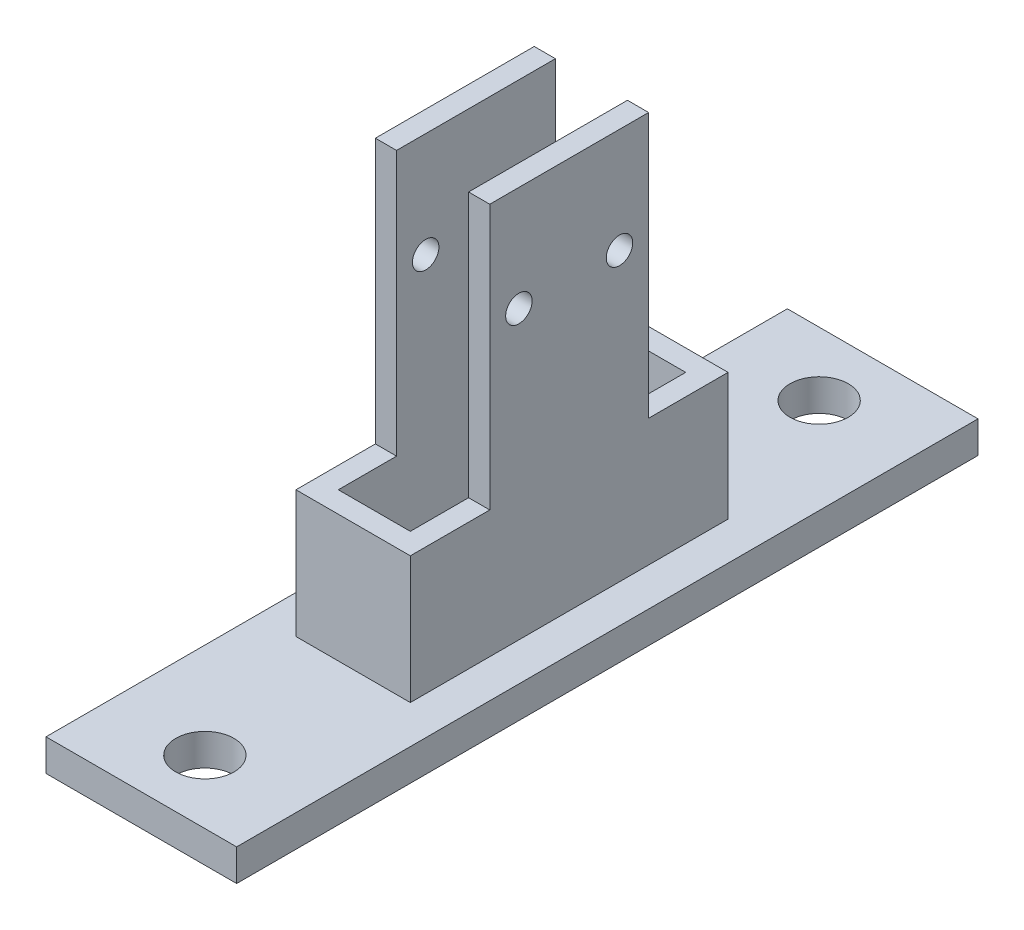
SolidWorks part; units mm, degrees
ref_plane "Front Plane" through (0, 0, 0) normal (0, 0, 1) x (1, 0, 0)
ref_plane "Top Plane" through (0, 0, 0) normal (0, 1, 0) x (1, 0, 0)
ref_plane "Right Plane" through (0, 0, 0) normal (1, 0, 0) x (0, 0, -1)
sketch "Sketch1" plane through (0, 0, 0) normal (0, 1, 0) x (1, 0, 0)
  line L1 (-22.5, 15) -> (22.5, 15)
  line L2 (-22.5, 15) -> (-22.5, -15)
  line L3 (-22.5, -15) -> (22.5, -15)
  line L4 (22.5, 15) -> (22.5, -15)
  line L5 (-22.5, 15) -> (22.5, -15) construction
  line L6 (-22.5, -15) -> (22.5, 15) construction
  point P0 (0, 0)
  dimension "D1" = 45
  dimension "D2" = 30
extrude "Boss-Extrude1" add sketch "Sketch1" along normal blind 3 contours L2 L1 L4 L3
ref_plane "Plane1" through (0, 0, -15) normal (0, 0, -1) x (-1, 0, 0)
ref_plane "Plane2" through (0, 0, 15) normal (0, 0, 1) x (1, 0, 0)
ref_plane "Plane3" through (3.4, 0, 0) normal (1, 0, 0) x (0, 0, -1)
ref_plane "Plane4" through (-3.4, 0, 0) normal (1, 0, 0) x (0, 0, -1)
sketch "Sketch3" plane through (-3.4, 0, 0) normal (1, 0, 0) x (0, 0, -1)
  line L0 (-15, 3) -> (-15, 0) construction
  line L1 (-7.5, 40) -> (7.5, 40)
  line L2 (-7.5, 40) -> (-7.5, 15)
  line L3 (-22.803, 0) -> (22.803, 0)
  line L4 (7.5, 40) -> (7.5, 15)
  line L7 (-7.5, 15) -> (-15, 15)
  line L8 (0, 0) -> (0, 40) construction
  line L9 (15, 0) -> (-15, 0) construction
  line L10 (15, 3) -> (15, 0) construction
  line L11 (15, 15) -> (7.5, 15)
  line L12 (15, 15) -> (15, 0)
  line L13 (15, 0) -> (-15, 0)
  line L14 (-15, 15) -> (-15, 0)
  line L15 (15, 15) -> (-15, 0) construction
  line L16 (15, 0) -> (-15, 15) construction
  circle A0 centre (-4.75, 30.1) radius 1.25
  circle A1 centre (4.75, 30.1) radius 1.25
  point P5 (0, 0)
  point P17 (0, 7.5)
  dimension "D3" = 2.5
  dimension "D1" = 40
  dimension "D2" = 15
  dimension "D4" = 9.5
  dimension "D5" = 4.75
  dimension "D6" = 30.1
  dimension "D7" = 15
extrude "Boss-Extrude2" add sketch "Sketch3" against normal blind 2 contours L7 L14 L13 L3 L12 L11 L4 L1 L2 A1 A0
mirror "Mirror1" about plane through (0, 0, 0) normal (1, 0, 0) of bodies 102
sketch "Sketch4" plane through (0, 0, 15) normal (0, 0, 1) x (1, 0, 0)
  line L1 (-5.4, 15) -> (5.4, 15)
  line L2 (-5.4, 15) -> (-5.4, 3)
  line L3 (-5.4, 3) -> (5.4, 3)
  line L4 (5.4, 15) -> (5.4, 3)
extrude "Boss-Extrude3" add sketch "Sketch4" against normal blind 2 contours L2 L1 L4 L3
mirror "Mirror2" about plane through (0, 0, 0) normal (0, 0, 1) of "Boss-Extrude3"
sketch "Sketch6" plane through (-5.4, 0, 0) normal (-1, 0, 0) x (0, 0, 1)
  line L0 (7.5, 40) -> (7.5, 15) construction
  line L1 (-7.5, 40) -> (7.5, 40)
  line L2 (-7.5, 40) -> (-7.5, 35.8403)
  line L3 (-7.5, 35.8403) -> (7.5, 35.8403)
  line L4 (7.5, 40) -> (7.5, 35.8403)
sketch "Sketch7" plane through (0, 3, 0) normal (0, 1, 0) x (1, 0, 0)
  line L0 (5.4, 15) -> (22.5, 15) construction
  line L1 (-12.5, 5) -> (12.5, 5)
  line L2 (-12.5, 5) -> (-12.5, -5)
  line L3 (-12.5, -5) -> (12.5, -5)
  line L4 (12.5, 5) -> (12.5, -5)
  line L5 (-12.5, 5) -> (12.5, -5) construction
  line L6 (-12.5, -5) -> (12.5, 5) construction
  line L7 (22.5, 15) -> (22.5, -15) construction
  point P0 (0, 0)
  dimension "D1" = 10
  dimension "D2" = 10
sketch "Sketch10" plane through (0, 3, 0) normal (0, 1, 0) x (1, 0, 0)
  line L1 (-9, 35) -> (9, 35)
  line L2 (-9, 35) -> (-9, -35)
  line L3 (-9, -35) -> (9, -35)
  line L4 (9, 35) -> (9, -35)
  line L5 (-9, 35) -> (9, -35) construction
  line L6 (-9, -35) -> (9, 35) construction
  point P0 (0, 0)
  dimension "D1" = 70
  dimension "D2" = 18
extrude "Boss-Extrude4" add sketch "Sketch10" against normal blind 3
sketch "Sketch11" plane through (0, 3, 0) normal (0, 1, 0) x (1, 0, 0)
  line L0 (-9, -15) -> (-9, -35) construction
  line L1 (-22.5, 15) -> (-9, 15)
  line L2 (-22.5, 15) -> (-22.5, -15)
  line L3 (-22.5, -15) -> (-9, -15)
  line L4 (-9, 15) -> (-9, -15)
  line L5 (-22.5, 15) -> (-9, -15) construction
  line L6 (-22.5, -15) -> (-9, 15) construction
  point P0 (-15.75, 0)
extrude "Cut-Extrude1" cut sketch "Sketch11" against normal blind 3
mirror "Mirror3" about plane through (0, 0, 0) normal (1, 0, 0) of "Cut-Extrude1"
sketch "Sketch12" plane through (0, 3, 0) normal (0, 1, 0) x (1, 0, 0)
  line L0 (0, 29) -> (0, -29) construction
  line L1 (-12.5, 5) -> (12.5, -5) construction
  line L2 (4.5, 29) -> (4.5, -29) construction
  line L3 (-4.5, 29) -> (-4.5, -29) construction
  arc A0 (4.5, 29) -> (-4.5, 29) centre (0, 29) ccw construction
  arc A1 (-4.5, -29) -> (4.5, -29) centre (0, -29) ccw construction
  point P4 (0, 0)
  point P11 (0, 29)
  point P13 (0, -29)
  dimension "D2" = 4.5
  dimension "D1" = 58
hole_wizard "M5 Clearance Hole1" positions "Sketch12" profile "Sketch13" hole size "M5" standard "ISO"
sketch "Sketch13" plane through (0, 3, 29) normal (1, 0, 0) x (0, 0, 1)
  line L0 (0, 0) -> (0, 3)
  line L1 (0, 3) -> (2.75, 3)
  line L2 (2.75, 3) -> (2.75, 0)
  line L5 (2.75, 0) -> (0, 0)
  line L11 (0, -6.35) -> (0, 107.95) construction
  dimension "Thru Hole Dia." = 5.5
  dimension "Thru Hole Depth" = 3
